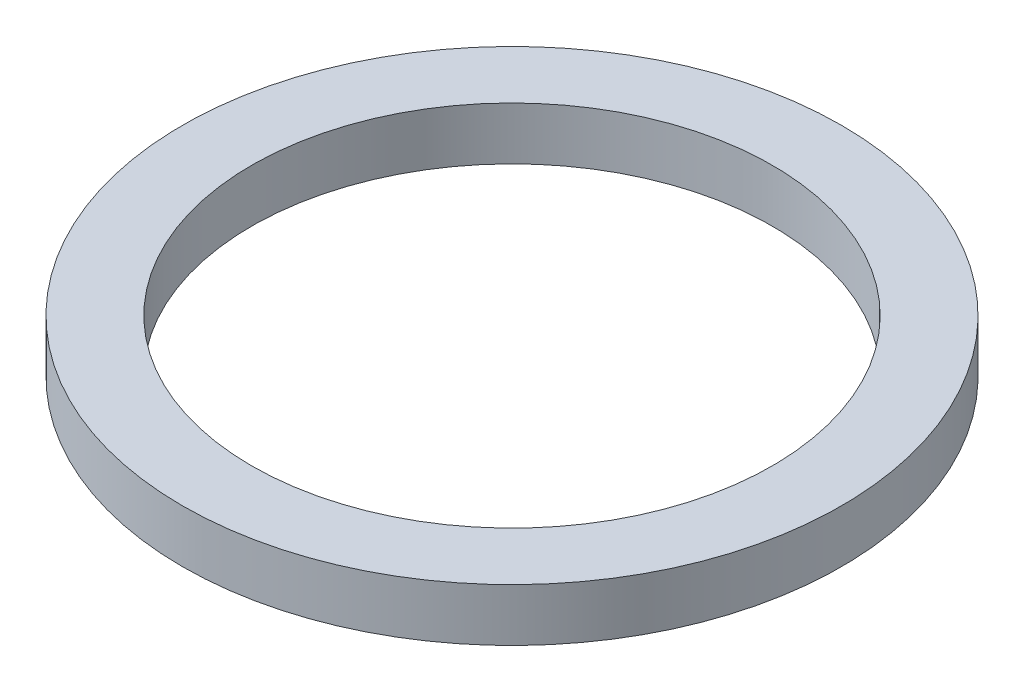
SolidWorks part; units mm, degrees
material "ABS"
ref_plane "Front Plane" through (0, 0, 0) normal (0, 0, 1) x (1, 0, 0)
ref_plane "Top Plane" through (0, 0, 0) normal (0, 1, 0) x (1, 0, 0)
ref_plane "Right Plane" through (0, 0, 0) normal (1, 0, 0) x (0, 0, -1)
sketch "Sketch1" plane through (0, 0, 0) normal (0, 1, 0) x (1, 0, 0)
  circle A0 centre (0, 0) radius 2.5082
  circle A1 centre (0, 0) radius 3.175
  dimension "D1" = 6.35
  dimension "D2" = 5.0165
extrude "Boss-Extrude1" add sketch "Sketch1" along normal blind 0.508
